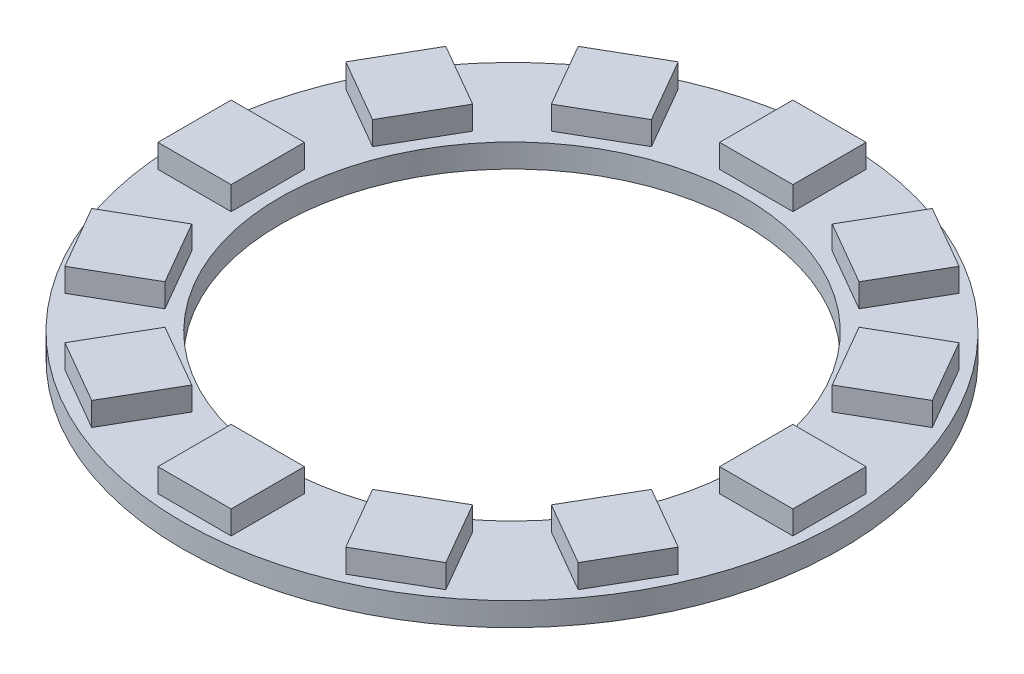
SolidWorks part; units mm, degrees
ref_plane "Front Plane" through (0, 0, 0) normal (0, 0, 1) x (1, 0, 0)
ref_plane "Top Plane" through (0, 0, 0) normal (0, 1, 0) x (1, 0, 0)
ref_plane "Right Plane" through (0, 0, 0) normal (1, 0, 0) x (0, 0, -1)
sketch "Sketch1" plane through (0, 0, 0) normal (0, 1, 0) x (1, 0, 0)
  circle A0 centre (0, 0) radius 22.5
  circle A1 centre (0, 0) radius 15.85
extrude "PCB" add sketch "Sketch1" along normal blind 1.6 from offset 32
sketch "Sketch2" plane through (0, 0, 0) normal (0, 1, 0) x (1, 0, 0)
  line L0 (16.675, 2.5) -> (21.675, 2.5)
  line L1 (21.675, 2.5) -> (21.675, -2.5)
  line L2 (21.675, -2.5) -> (16.675, -2.5)
  line L3 (16.675, -2.5) -> (16.675, 2.5)
  line L4 (15.691, -6.1724) -> (20.0211, -8.6724)
  line L5 (20.0211, -8.6724) -> (17.5211, -13.0026)
  line L6 (17.5211, -13.0026) -> (13.191, -10.5026)
  line L7 (13.191, -10.5026) -> (15.691, -6.1724)
  line L8 (10.5026, -13.191) -> (13.0026, -17.5211)
  line L9 (13.0026, -17.5211) -> (8.6724, -20.0211)
  line L10 (8.6724, -20.0211) -> (6.1724, -15.691)
  line L11 (6.1724, -15.691) -> (10.5026, -13.191)
  line L12 (2.5, -16.675) -> (2.5, -21.675)
  line L13 (2.5, -21.675) -> (-2.5, -21.675)
  line L14 (-2.5, -21.675) -> (-2.5, -16.675)
  line L15 (-2.5, -16.675) -> (2.5, -16.675)
  line L16 (-6.1724, -15.691) -> (-8.6724, -20.0211)
  line L17 (-8.6724, -20.0211) -> (-13.0026, -17.5211)
  line L18 (-13.0026, -17.5211) -> (-10.5026, -13.191)
  line L19 (-10.5026, -13.191) -> (-6.1724, -15.691)
  line L20 (-13.191, -10.5026) -> (-17.5211, -13.0026)
  line L21 (-17.5211, -13.0026) -> (-20.0211, -8.6724)
  line L22 (-20.0211, -8.6724) -> (-15.691, -6.1724)
  line L23 (-15.691, -6.1724) -> (-13.191, -10.5026)
  line L24 (-16.675, -2.5) -> (-21.675, -2.5)
  line L25 (-21.675, -2.5) -> (-21.675, 2.5)
  line L26 (-21.675, 2.5) -> (-16.675, 2.5)
  line L27 (-16.675, 2.5) -> (-16.675, -2.5)
  line L28 (-15.691, 6.1724) -> (-20.0211, 8.6724)
  line L29 (-20.0211, 8.6724) -> (-17.5211, 13.0026)
  line L30 (-17.5211, 13.0026) -> (-13.191, 10.5026)
  line L31 (-13.191, 10.5026) -> (-15.691, 6.1724)
  line L32 (-10.5026, 13.191) -> (-13.0026, 17.5211)
  line L33 (-13.0026, 17.5211) -> (-8.6724, 20.0211)
  line L34 (-8.6724, 20.0211) -> (-6.1724, 15.691)
  line L35 (-6.1724, 15.691) -> (-10.5026, 13.191)
  line L36 (-2.5, 16.675) -> (-2.5, 21.675)
  line L37 (-2.5, 21.675) -> (2.5, 21.675)
  line L38 (2.5, 21.675) -> (2.5, 16.675)
  line L39 (2.5, 16.675) -> (-2.5, 16.675)
  line L40 (6.1724, 15.691) -> (8.6724, 20.0211)
  line L41 (8.6724, 20.0211) -> (13.0026, 17.5211)
  line L42 (13.0026, 17.5211) -> (10.5026, 13.191)
  line L43 (10.5026, 13.191) -> (6.1724, 15.691)
  line L44 (13.191, 10.5026) -> (17.5211, 13.0026)
  line L45 (17.5211, 13.0026) -> (20.0211, 8.6724)
  line L46 (20.0211, 8.6724) -> (15.691, 6.1724)
  line L47 (15.691, 6.1724) -> (13.191, 10.5026)
extrude "LEDs" add sketch "Sketch2" along normal blind 1.6 from offset 33.6
